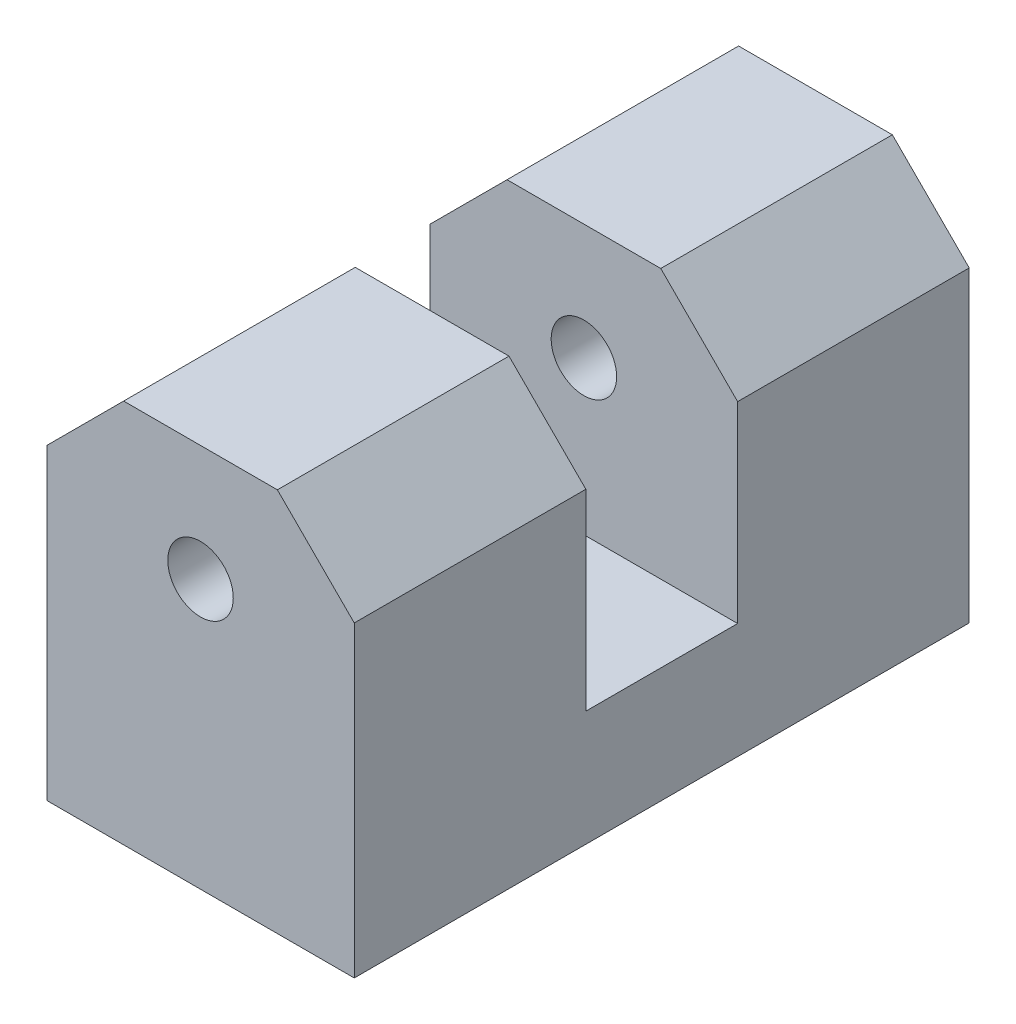
SolidWorks part; units mm, degrees
ref_plane "Спереди" through (0, 0, 0) normal (0, 0, 1) x (1, 0, 0)
ref_plane "Сверху" through (0, 0, 0) normal (0, 1, 0) x (1, 0, 0)
ref_plane "Справа" through (0, 0, 0) normal (1, 0, 0) x (0, 0, -1)
sketch "Эскиз1" plane through (0, 0, 0) normal (0, 1, 0) x (1, 0, 0)
  line L1 (-4, 8) -> (4, 8)
  line L2 (-4, 8) -> (-4, -8)
  line L3 (-4, -8) -> (4, -8)
  line L4 (4, 8) -> (4, -8)
  line L5 (-4, 8) -> (4, -8) construction
  line L6 (-4, -8) -> (4, 8) construction
  point P0 (0, 0)
extrude "Вытянуть1" add sketch "Эскиз1" along normal blind 10
sketch "Эскиз2" plane through (0, 0, 8) normal (0, 0, 1) x (1, 0, 0)
  circle A0 centre (0, 6.9864) radius 0.852
extrude "Вырез-Вытянуть1" cut sketch "Эскиз2" against normal through all
sketch "Эскиз3" plane through (0, 10, 0) normal (0, 1, 0) x (1, 0, 0)
  line L0 (5, 0) -> (11.308, 0) construction
  line L3 (-5.6178, 1.9745) -> (5.6178, 1.9745)
  line L4 (-5.6178, 1.9745) -> (-5.6178, -1.9745)
  line L5 (-5.6178, -1.9745) -> (5.6178, -1.9745)
  line L6 (5.6178, 1.9745) -> (5.6178, -1.9745)
  line L7 (-5.6178, 1.9745) -> (5.6178, -1.9745) construction
  line L8 (-5.6178, -1.9745) -> (5.6178, 1.9745) construction
  point P1 (0, 0)
extrude "Вырез-Вытянуть2" cut sketch "Эскиз3" against normal blind 7
chamfer "Фаска1" distance 2 angle 45 4 edges at (-4, 10, -4.9873) (-4, 10, 4.9873) (4, 10, -4.9873) (4, 10, 4.9873)
